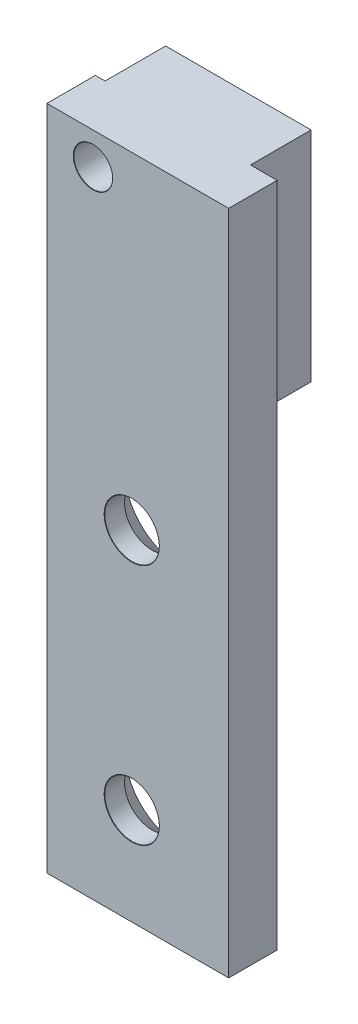
SolidWorks part; units mm, degrees
material "ABS"
ref_plane "Front Plane" through (0, 0, 0) normal (0, 0, 1) x (1, 0, 0)
ref_plane "Top Plane" through (0, 0, 0) normal (0, 1, 0) x (1, 0, 0)
ref_plane "Right Plane" through (0, 0, 0) normal (1, 0, 0) x (0, 0, -1)
sketch "Sketch1" plane through (0, 0, 0) normal (0, 0, 1) x (1, 0, 0)
  line L1 (7.5, -27.5) -> (-7.5, -27.5)
  line L2 (7.5, -27.5) -> (7.5, 27.5)
  line L3 (7.5, 27.5) -> (-7.5, 27.5)
  line L4 (-7.5, -27.5) -> (-7.5, 27.5)
  line L5 (7.5, -27.5) -> (-7.5, 27.5) construction
  line L6 (7.5, 27.5) -> (-7.5, -27.5) construction
  point P0 (0, 0)
  dimension "D1" = 55
  dimension "D2" = 15
extrude "Boss-Extrude1" add sketch "Sketch1" along normal blind 4
hole_wizard "CSK for M4 Hex Socket Countersunk Head Screw1" positions "Sketch3" profile "Sketch5" countersink size "M4" standard "DIN" end condition up to next
sketch "Sketch3" plane through (0, 0, 0) normal (0, 0, -1) x (-1, 0, 0)
  line L9 (7.5, -27.5) -> (-7.5, -27.5) construction
  line L10 (-7.5, -27.5) -> (-7.5, 27.5) construction
  point P0 (0.5, 0.5)
  point P2 (0.5, -19.5)
  dimension "D1" = 20
  dimension "D2" = 8
  dimension "D3" = 8
sketch "Sketch5" plane through (-0.5, 0.5, 0) normal (1, 0, 0) x (0, 1, 0)
  line L0 (0, 0) -> (0, 4)
  line L1 (0, 4) -> (2.275, 4)
  line L2 (2.25, 3.975) -> (2.25, 2.34)
  line L3 (2.25, 2.34) -> (4.59, 0)
  line L5 (4.59, 0) -> (0, 0)
  line L6 (-2.25, 2.34) -> (-4.59, 0) construction
  line L7 (2.275, 4) -> (2.25, 3.975)
  line L8 (-2.275, 4) -> (-2.25, 3.975) construction
  line L11 (0, -6.35) -> (0, 107.95) construction
  dimension "Thru Hole Dia." = 4.5
  dimension "Thru Hole Depth" = 4
  dimension "Near C'Sink Dia." = 9.18
  dimension "Near C'Sink Angle" = 90
  dimension "Far C'Sink Dia." = 4.55
  dimension "Far C'Sink Angle" = 90
sketch "Sketch15" plane through (0, 0, 0) normal (0, 0, -1) x (-1, 0, 0)
  line L0 (-7.5, 27.5) -> (7.5, 27.5) construction
  line L1 (-5.3, 27.5) -> (6.7, 27.5)
  line L2 (-5.3, 27.5) -> (-5.3, 9.5)
  line L3 (-5.3, 9.5) -> (6.7, 9.5)
  line L4 (6.7, 27.5) -> (6.7, 9.5)
  line L5 (-7.5, -27.5) -> (-7.5, 27.5) construction
  dimension "D1" = 18
  dimension "D2" = 12
  dimension "D3" = 2.2
extrude "Boss-Extrude2" add sketch "Sketch15" along normal blind 5
hole_wizard "M3 Clearance Hole1" positions "Sketch18" profile "Sketch19" hole size "M3" standard "DIN" end condition up to next
sketch "Sketch18" plane through (0, 0, -5) normal (0, 0, -1) x (-1, 0, 0)
  line L0 (6.7, 9.5) -> (6.7, 27.5) construction
  line L2 (6.7, 27.5) -> (-5.3, 27.5) construction
  point P0 (3.7, 24.85)
  dimension "D1" = 3
  dimension "D2" = 2.65
sketch "Sketch19" plane through (-3.7, 24.85, -5) normal (1, 0, 0) x (0, 1, 0)
  line L0 (0, 0) -> (0, 9)
  line L1 (0, 9) -> (1.625, 9)
  line L2 (1.6, 8.975) -> (1.6, 0)
  line L5 (1.6, 0) -> (0, 0)
  line L7 (1.625, 9) -> (1.6, 8.975)
  line L8 (-1.625, 9) -> (-1.6, 8.975) construction
  line L11 (0, -6.35) -> (0, 107.95) construction
  dimension "Thru Hole Dia." = 3.2
  dimension "Thru Hole Depth" = 9
  dimension "Far C'Sink Dia." = 3.25
  dimension "Far C'Sink Angle" = 90
